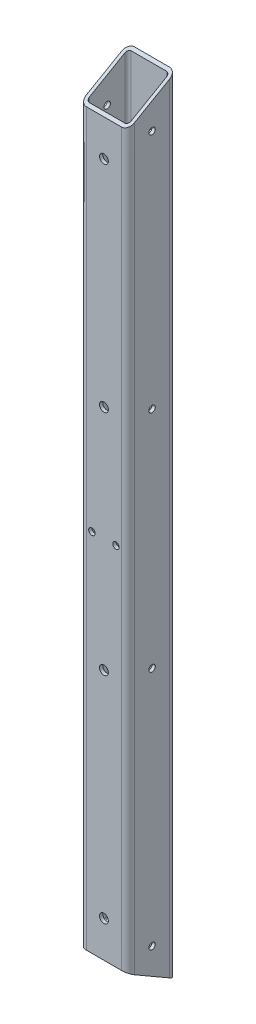
SolidWorks part; units mm, degrees
material "AISI 1010 钢，热轧条材"
ref_plane "前视基准面" through (0, 0, 0) normal (0, 0, 1) x (1, 0, 0)
ref_plane "上视基准面" through (0, 0, 0) normal (0, 1, 0) x (1, 0, 0)
ref_plane "右视基准面" through (0, 0, 0) normal (1, 0, 0) x (0, 0, -1)
sketch "草图1" plane through (0, 0, 0) normal (0, 1, 0) x (1, 0, 0)
  line L0 (4, 2) -> (26, 2)
  line L1 (4, 0) -> (26, 0)
  line L2 (0, 4) -> (0, 26)
  line L3 (4, 30) -> (26, 30)
  line L4 (30, 4) -> (30, 26)
  line L5 (28, 4) -> (28, 26)
  line L6 (4, 28) -> (26, 28)
  line L7 (2, 4) -> (2, 26)
  arc A0 (4, 0) -> (0, 4) centre (4, 4) cw
  arc A1 (26, 0) -> (30, 4) centre (26, 4) ccw
  arc A2 (26, 30) -> (30, 26) centre (26, 26) cw
  arc A3 (0, 26) -> (4, 30) centre (4, 26) cw
  arc A4 (26, 2) -> (28, 4) centre (26, 4) ccw
  arc A5 (26, 28) -> (28, 26) centre (26, 26) cw
  arc A6 (2, 26) -> (4, 28) centre (4, 26) cw
  arc A7 (4, 2) -> (2, 4) centre (4, 4) cw
  point P7 (0, 0)
  point P10 (30, 0)
  point P13 (30, 30)
  point P16 (0, 30)
  dimension "D3" = 4
  dimension "D1" = 30
  dimension "D2" = 30
  dimension "D4" = 2
extrude "凸台-拉伸1" add sketch "草图1" along normal mid plane 490
sketch "草图2" plane through (0, 0, 0) normal (0, 0, -1) x (-1, 0, 0)
  line L0 (0, 245) -> (0, -245) construction
  line L1 (-26, 245) -> (-4, 245) construction
  line L2 (0, 0) -> (-30, 0) construction
  line L3 (-30, 245) -> (-30, -245) construction
  circle A0 centre (-22.5, 0) radius 2
  circle A1 centre (-7.5, 0) radius 2
  circle A2 centre (-15, 205) radius 2.75
  circle A3 centre (-15, 71) radius 2.75
  circle A4 centre (-15, -71) radius 2.75
  circle A5 centre (-15, -205) radius 2.75
  point P15 (-15, 245)
  dimension "D1" = 4
  dimension "D4" = 5.5
  dimension "D2" = 15
  dimension "D3" = 7.5
  dimension "D5" = 134
  dimension "D6" = 40
extrude "切除-拉伸1" cut sketch "草图2" along normal through all
sketch "草图3" plane through (0, 0, 0) normal (1, 0, 0) x (0, 0, -1)
  line L0 (0, 0) -> (30, 0) construction
  line L1 (30, 245) -> (30, -245) construction
  line L8 (30, 245) -> (0, 227.6795)
  line L9 (0, 245) -> (0, -245) construction
  line L10 (0, 227.6795) -> (0, 245)
  line L11 (0, 245) -> (30, 245)
  line L12 (0, -245) -> (30, -245)
  line L13 (0, -227.6795) -> (0, -245)
  line L14 (30, -245) -> (0, -227.6795)
  dimension "D1" = 60
extrude "切除-拉伸3" cut sketch "草图3" against normal through all and the other way through all
sketch "草图4" plane through (0, 0, 0) normal (1, 0, 0) x (0, 0, -1)
  line L1 (0, 227.6795) -> (0, -227.6795) construction
  line L2 (0, 0) -> (30, 0) construction
  line L3 (30, 245) -> (30, -245) construction
  circle A0 centre (15, 220) radius 2
  circle A1 centre (15, 70) radius 2
  circle A2 centre (15, -70) radius 2
  circle A3 centre (15, -220) radius 2
  dimension "D1" = 4
  dimension "D2" = 25
  dimension "D3" = 15
  dimension "D4" = 70
extrude "切除-拉伸4" cut sketch "草图4" along normal through all
